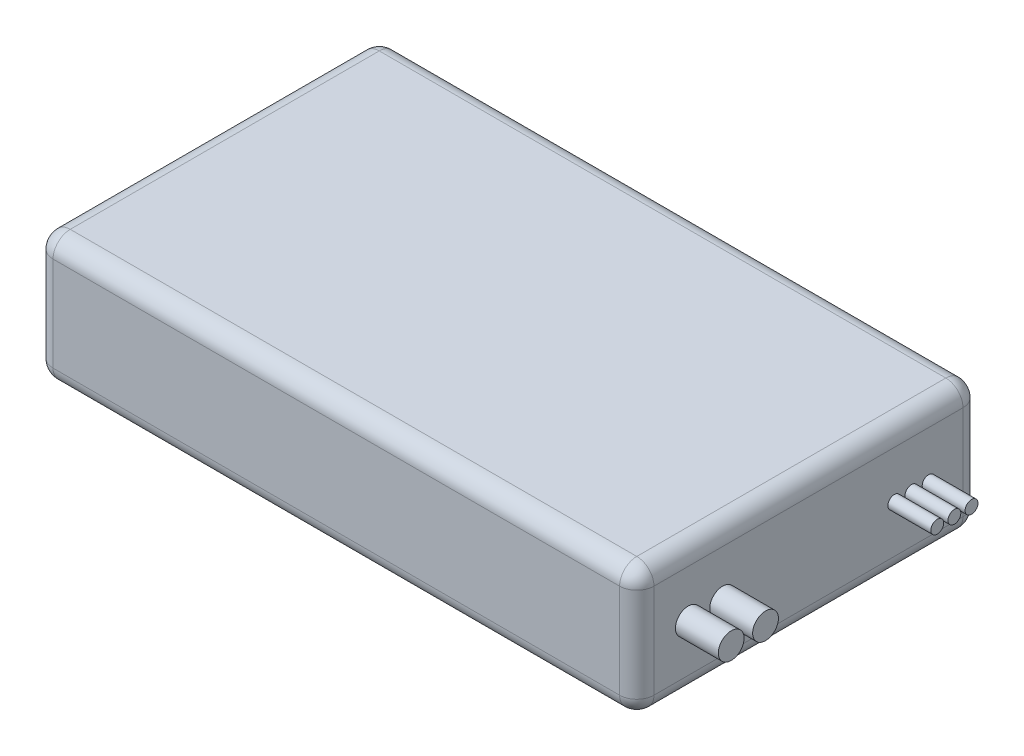
SolidWorks part; units mm, degrees
ref_plane "Plan de face" through (0, 0, 0) normal (0, 0, 1) x (1, 0, 0)
ref_plane "Plan de dessus" through (0, 0, 0) normal (0, 1, 0) x (1, 0, 0)
ref_plane "Plan de droite" through (0, 0, 0) normal (1, 0, 0) x (0, 0, -1)
sketch "Esquisse1" plane through (0, 0, 0) normal (0, 1, 0) x (1, 0, 0)
  line L1 (0, 0) -> (70, 0)
  line L2 (0, 0) -> (0, 40)
  line L3 (0, 40) -> (70, 40)
  line L4 (70, 0) -> (70, 40)
  dimension "D1" = 70
  dimension "D2" = 40
extrude "Extrusion1" add sketch "Esquisse1" along normal blind 15
fillet "Congé1" radius 2 12 edges at (0, 0, -20) (35, 0, -40) (0, 7.5, -40) (0, 7.5, 0) (70, 7.5, 0) (70, 7.5, -40) (70, 0, -20) (70, 15, -20) (35, 15, -40) (0, 15, -20) (35, 0, 0) (35, 15, 0)
sketch "Esquisse2" plane through (70, 0, 0) normal (1, 0, 0) x (0, 0, -1)
  line L0 (2, 7.5) -> (38, 7.5) construction
  line L1 (2, 13) -> (2, 2) construction
  line L2 (38, 2) -> (38, 13) construction
  line L3 (20, 13) -> (20, 2) construction
  line L4 (38, 13) -> (2, 13) construction
  line L5 (2, 2) -> (38, 2) construction
  circle A0 centre (6, 7.5) radius 1.5
  circle A1 centre (10, 7.5) radius 1.5
  circle A2 centre (30, 7.5) radius 0.75
  circle A3 centre (32, 7.5) radius 0.75
  circle A4 centre (34, 7.5) radius 0.75
  dimension "D1" = 3
  dimension "D2" = 1.5
  dimension "D3" = 4
  dimension "D4" = 10
  dimension "D5" = 2
  dimension "D6" = 2
  dimension "D7" = 10
extrude "Extrusion2" add sketch "Esquisse2" along normal blind 5
